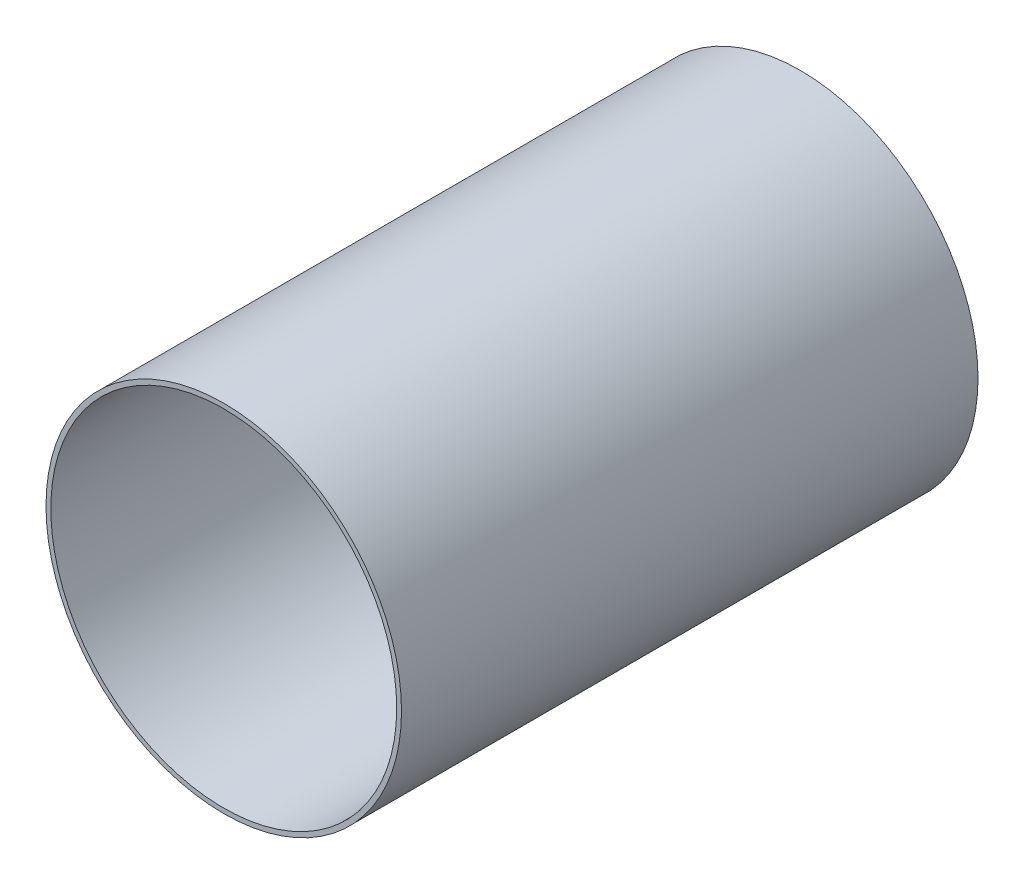
SolidWorks part; units mm, degrees
ref_plane "前视基准面" through (0, 0, 0) normal (0, 0, 1) x (1, 0, 0)
ref_plane "上视基准面" through (0, 0, 0) normal (0, 1, 0) x (1, 0, 0)
ref_plane "右视基准面" through (0, 0, 0) normal (1, 0, 0) x (0, 0, -1)
other "Configuration Table"
sketch "草图1" plane through (0, 0, 0) normal (0, 0, 1) x (1, 0, 0)
  circle A0 centre (0, 0) radius 90
  circle A1 centre (0, 0) radius 92.5
  dimension "D1" = 180
  dimension "D2" = 185
extrude "凸台-拉伸1" add sketch "草图1" along normal blind 300
